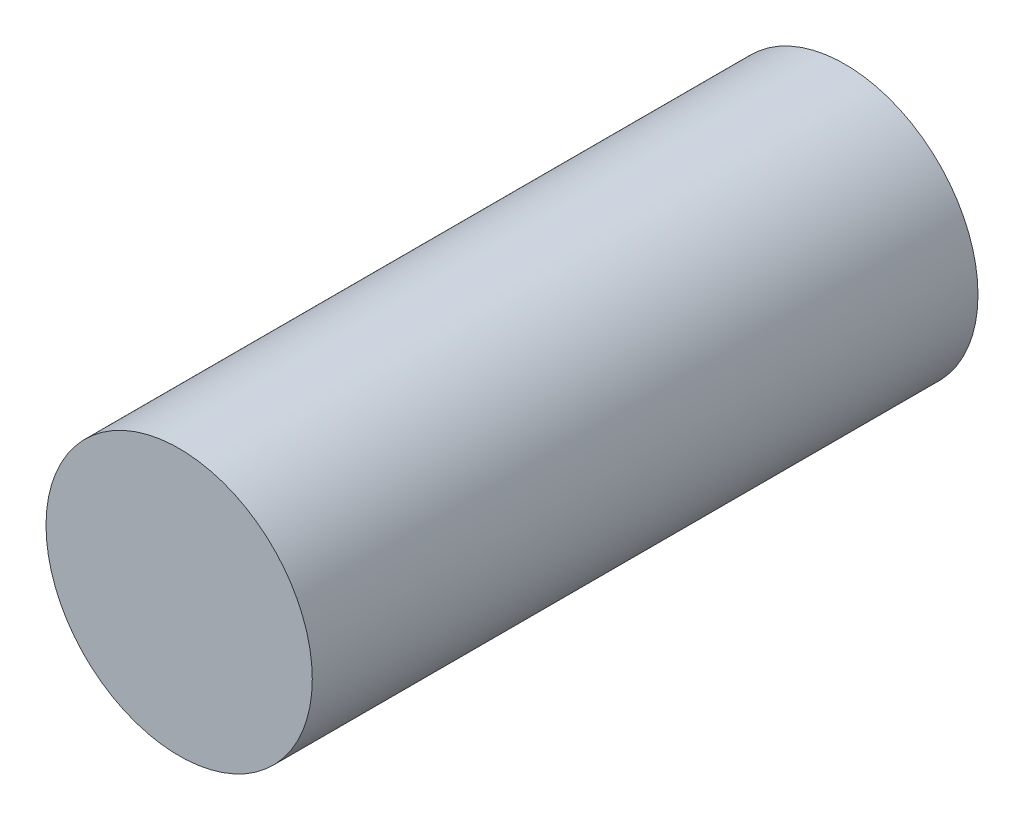
SolidWorks part; units mm, degrees
ref_plane "Front Plane" through (0, 0, 0) normal (0, 0, 1) x (1, 0, 0)
ref_plane "Top Plane" through (0, 0, 0) normal (0, 1, 0) x (1, 0, 0)
ref_plane "Right Plane" through (0, 0, 0) normal (1, 0, 0) x (0, 0, -1)
sketch "Sketch1" plane through (0, 0, 0) normal (0, 0, 1) x (1, 0, 0)
  circle A0 centre (0, 0) radius 20
  dimension "D1" = 40
extrude "Boss-Extrude1" add sketch "Sketch1" along normal blind 100
